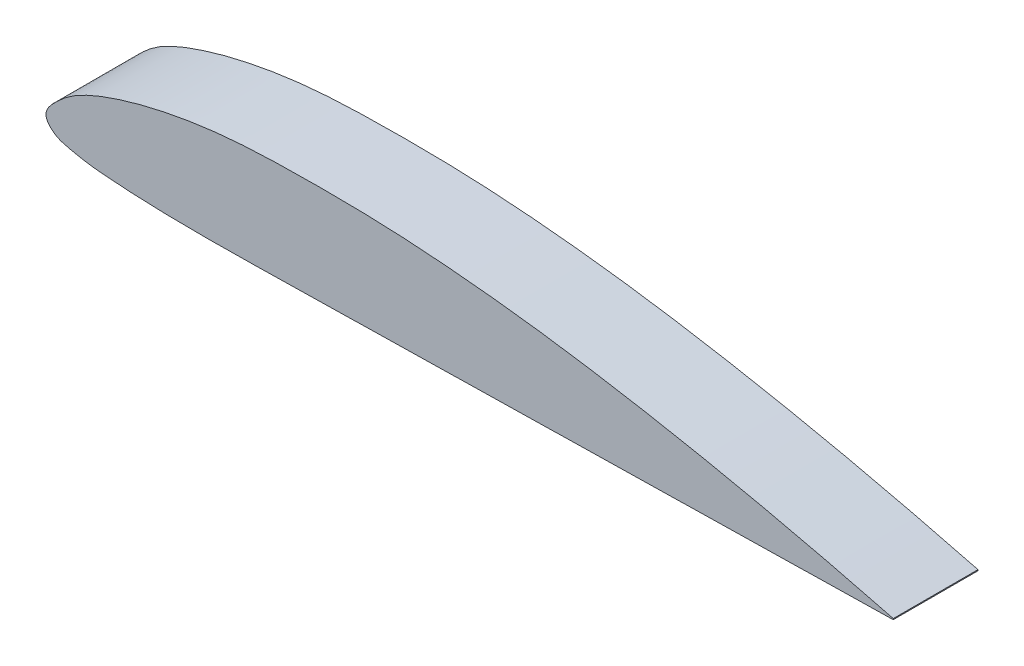
SolidWorks part; units mm, degrees
ref_plane "Front Plane" through (0, 0, 0) normal (0, 0, 1) x (1, 0, 0)
ref_plane "Top Plane" through (0, 0, 0) normal (0, 1, 0) x (1, 0, 0)
ref_plane "Right Plane" through (0, 0, 0) normal (1, 0, 0) x (0, 0, -1)
curve "Curve1"
  spline degree 3 poles (25.4, 0.0152, 0) (25.3153, 0.0353, 0) (25.146, 0.0754, 0) (24.892, 0.1355, 0) (24.6381, 0.1953, 0) (24.2995, 0.2744, 0) (23.8763, 0.3719, 0) (23.3683, 0.4859, 0) (22.8603, 0.5973, 0) (22.3523, 0.7062, 0) (21.8443, 0.8125, 0) (21.3363, 0.9162, 0) (20.8283, 1.017, 0) (20.3203, 1.1151, 0) (19.8123, 1.2102, 0) (19.3043, 1.3024, 0) (18.7962, 1.3915, 0) (18.2882, 1.4777, 0) (17.7802, 1.5609, 0) (17.2722, 1.6409, 0) (16.7643, 1.7177, 0) (16.2563, 1.7908, 0) (15.7483, 1.8601, 0) (15.2403, 1.9251, 0) (14.7323, 1.9856, 0) (14.2242, 2.0416, 0) (13.7162, 2.093, 0) (13.2082, 2.1398, 0) (12.7002, 2.182, 0) (12.1922, 2.2197, 0) (11.6842, 2.2524, 0) (11.1761, 2.2798, 0) (10.6681, 2.3014, 0) (10.1601, 2.3168, 0) (9.652, 2.3257, 0) (9.144, 2.3283, 0) (8.636, 2.3252, 0) (8.128, 2.3169, 0) (7.6199, 2.3039, 0) (7.1119, 2.2871, 0) (6.6038, 2.2641, 0) (6.0956, 2.2327, 0) (5.5873, 2.1902, 0) (5.079, 2.1342, 0) (4.5707, 2.0617, 0) (4.0625, 1.9727, 0) (3.5542, 1.8677, 0) (3.0455, 1.7457, 0) (2.5366, 1.6033, 0) (2.0278, 1.436, 0) (1.6043, 1.2762, 0) (1.2667, 1.1258, 0) (1.0109, 0.9949, 0) (0.7528, 0.8393, 0) (0.5145, 0.6577, 0) (0.3356, 0.4854, 0) (0.199, 0.3469, 0) (0.1123, 0.2457, 0) (0.0552, 0.1586, 0) (0.0273, 0.1015, 0) (0.0095, 0.0523, 0) (-0.0066, -0.0188, 0) (0.0016, -0.0927, 0) (0.0273, -0.1571, 0) (0.0549, -0.2082, 0) (0.1111, -0.2828, 0) (0.1967, -0.3619, 0) (0.3302, -0.4523, 0) (0.5196, -0.5255, 0) (0.7613, -0.5742, 0) (1.0151, -0.6246, 0) (1.2693, -0.6634, 0) (1.608, -0.6993, 0) (2.0318, -0.7237, 0) (2.5398, -0.7478, 0) (3.0479, -0.7623, 0) (3.556, -0.7692, 0) (4.064, -0.7694, 0) (4.572, -0.764, 0) (5.08, -0.7541, 0) (5.588, -0.7407, 0) (6.096, -0.7247, 0) (6.604, -0.7067, 0) (7.112, -0.6877, 0) (7.62, -0.6682, 0) (8.128, -0.6491, 0) (8.636, -0.6304, 0) (9.144, -0.6118, 0) (9.652, -0.5934, 0) (10.16, -0.5749, 0) (10.668, -0.5564, 0) (11.176, -0.5378, 0) (11.684, -0.519, 0) (12.192, -0.5004, 0) (12.7, -0.4816, 0) (13.208, -0.4629, 0) (13.716, -0.4443, 0) (14.224, -0.4256, 0) (14.732, -0.407, 0) (15.24, -0.3883, 0) (15.748, -0.3697, 0) (16.256, -0.3511, 0) (16.764, -0.3324, 0) (17.272, -0.3137, 0) (17.78, -0.2951, 0) (18.288, -0.2764, 0) (18.796, -0.2578, 0) (19.304, -0.2391, 0) (19.812, -0.2205, 0) (20.32, -0.2018, 0) (20.828, -0.1831, 0) (21.336, -0.1645, 0) (21.844, -0.1458, 0) (22.352, -0.1271, 0) (22.86, -0.1085, 0) (23.368, -0.0898, 0) (23.876, -0.0712, 0) (24.2993, -0.0556, 0) (24.638, -0.0432, 0) (24.892, -0.0339, 0) (25.146, -0.0246, 0) (25.3153, -0.0183, 0) (25.4, -0.0152, 0) knots 0 0 0 0 0.005028 0.010055 0.015081 0.020105 0.030145 0.040174 0.050191 0.060198 0.070194 0.08018 0.090156 0.100121 0.110076 0.12002 0.129954 0.139879 0.149793 0.159699 0.169594 0.17948 0.189355 0.199219 0.209073 0.218917 0.228751 0.238577 0.248396 0.258207 0.268012 0.277811 0.287604 0.297393 0.307179 0.316964 0.326749 0.336535 0.346322 0.356113 0.365908 0.375711 0.385531 0.395376 0.405259 0.415192 0.425184 0.435248 0.445412 0.455711 0.466191 0.471552 0.477055 0.482787 0.488946 0.494316 0.497126 0.500187 0.502001 0.503128 0.50385 0.50502 0.507318 0.507987 0.509024 0.510668 0.513358 0.515716 0.519949 0.524973 0.529954 0.534903 0.539824 0.54963 0.559425 0.569214 0.579 0.588784 0.59857 0.608356 0.618144 0.627933 0.637724 0.647515 0.657307 0.667099 0.67689 0.686681 0.696472 0.706263 0.716054 0.725846 0.735637 0.745428 0.755219 0.765011 0.774802 0.784593 0.794384 0.804176 0.813967 0.823758 0.833549 0.84334 0.853132 0.862923 0.872714 0.882505 0.892297 0.902088 0.911879 0.92167 0.931461 0.941253 0.951044 0.960835 0.970626 0.980418 0.985313 0.990209 0.995104 1 1 1 1
sketch "Sketch3" plane through (0, 0, 0) normal (0, 0, 1) x (1, 0, 0)
  line L0 (36.0244, 8.8339) -> (36.0239, 8.8035)
  line L2 (36.0241, 8.8187) -> (10.6259, 9.2321) construction
  spline S1 degree 3 poles (36.0244, 8.8339) (35.9401, 8.8554) (35.7715, 8.8985) (35.5186, 8.963) (35.2657, 9.0273) (34.9286, 9.1123) (34.5072, 9.2171) (34.0012, 9.34) (33.4952, 9.4602) (32.9892, 9.578) (32.4831, 9.6931) (31.977, 9.8057) (31.4709, 9.9153) (30.9647, 10.0223) (30.4584, 10.1262) (29.9521, 10.2273) (29.4457, 10.3252) (28.9393, 10.4203) (28.4328, 10.5123) (27.9263, 10.6012) (27.4197, 10.6869) (26.9131, 10.7688) (26.4064, 10.847) (25.8996, 10.9208) (25.2241, 11.0133) (24.548, 11.0966) (23.8715, 11.1709) (23.3643, 11.222) (22.8571, 11.2685) (22.1808, 11.324) (21.5041, 11.3687) (20.827, 11.4011) (20.3192, 11.4188) (19.8113, 11.4303) (19.3033, 11.4361) (18.7952, 11.4367) (18.287, 11.4325) (17.7787, 11.4246) (17.2703, 11.4105) (16.7617, 11.388) (16.2527, 11.3543) (15.7435, 11.3072) (15.234, 11.2436) (14.7243, 11.1634) (14.2142, 11.0673) (13.7035, 10.9543) (13.1922, 10.8207) (12.6805, 10.6623) (12.2543, 10.51) (11.9142, 10.3655) (11.6561, 10.2391) (11.3954, 10.088) (11.1539, 9.9106) (10.972, 9.7415) (10.833, 9.6054) (10.7445, 9.5057) (10.686, 9.4195) (10.6571, 9.3629) (10.6384, 9.3141) (10.621, 9.2433) (10.628, 9.1693) (10.6526, 9.1045) (10.6793, 9.0528) (10.7341, 8.9772) (10.8183, 8.8967) (10.9502, 8.804) (11.1384, 8.7275) (11.3792, 8.6746) (11.6321, 8.6197) (11.8855, 8.5765) (12.2236, 8.5347) (12.6469, 8.5029) (13.1544, 8.4699) (13.6622, 8.4466) (14.17, 8.4308) (14.678, 8.4217) (15.186, 8.4183) (15.8635, 8.4197) (16.5411, 8.428) (17.2187, 8.4401) (17.7269, 8.4503) (18.2352, 8.4609) (18.7434, 8.4712) (19.2517, 8.481) (19.7599, 8.4907) (20.2682, 8.5002) (20.7764, 8.5098) (21.2847, 8.5195) (21.7929, 8.5292) (22.3012, 8.5391) (22.8094, 8.5489) (23.3177, 8.5588) (23.8259, 8.5686) (24.3342, 8.5784) (25.1813, 8.5947) (26.0283, 8.611) (27.0448, 8.6305) (27.7225, 8.6436) (28.4002, 8.6566) (28.9084, 8.6665) (29.4167, 8.6762) (29.9249, 8.686) (30.4332, 8.6958) (30.9414, 8.7056) (31.4496, 8.7154) (31.9579, 8.7252) (32.4661, 8.7349) (32.9744, 8.7448) (33.4826, 8.7545) (33.9909, 8.7643) (34.4991, 8.7741) (34.9227, 8.7823) (35.2615, 8.7888) (35.5156, 8.7937) (35.7698, 8.7985) (35.9392, 8.8018) (36.0239, 8.8035) knots 0 0 0 0 0.005028 0.010055 0.015081 0.020105 0.030145 0.040174 0.050191 0.060198 0.070194 0.08018 0.090156 0.100121 0.110076 0.12002 0.129954 0.139879 0.149793 0.159699 0.169594 0.17948 0.189355 0.199219 0.209073 0.228751 0.238577 0.248396 0.258207 0.268012 0.287604 0.297393 0.307179 0.316964 0.326749 0.336535 0.346322 0.356113 0.365908 0.375711 0.385531 0.395376 0.405259 0.415192 0.425184 0.435248 0.445412 0.455711 0.466191 0.471552 0.477055 0.482787 0.488946 0.494316 0.497126 0.500187 0.502001 0.503128 0.50385 0.50502 0.507318 0.507987 0.509024 0.510668 0.513358 0.515716 0.519949 0.524973 0.529954 0.534903 0.539824 0.54963 0.559425 0.569214 0.579 0.588784 0.59857 0.608356 0.627933 0.637724 0.647515 0.657307 0.667099 0.67689 0.686681 0.696472 0.706263 0.716054 0.725846 0.735637 0.745428 0.755219 0.765011 0.774802 0.784593 0.813967 0.823758 0.84334 0.853132 0.862923 0.872714 0.882505 0.892297 0.902088 0.911879 0.92167 0.931461 0.941253 0.951044 0.960835 0.970626 0.980418 0.985313 0.990209 0.995104 1 1 1 1
extrude "Boss-Extrude2" add sketch "Sketch3" along normal blind 2.54
